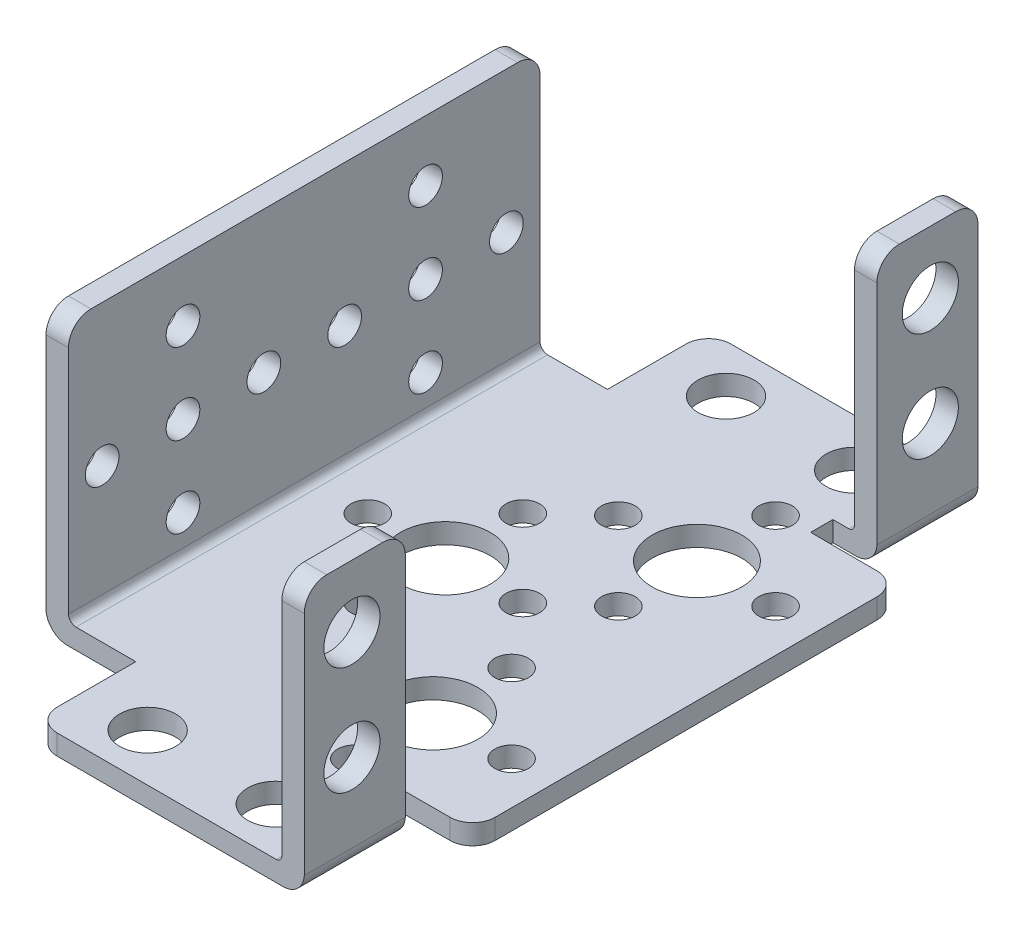
SolidWorks part; units mm, degrees
material "1060 Alloy"
ref_plane "Front Plane" through (0, 0, 0) normal (0, 0, 1) x (1, 0, 0)
ref_plane "Top Plane" through (0, 0, 0) normal (0, 1, 0) x (1, 0, 0)
ref_plane "Right Plane" through (0, 0, 0) normal (1, 0, 0) x (0, 0, -1)
sketch "Sketch2" plane through (0, 0, 0) normal (0, 0, 1) x (1, 0, 0)
  line L0 (1.7922, 0) -> (36, 0)
  line L1 (0, 1.7922) -> (0, 25)
  line L2 (0, 25) -> (2, 25)
  line L3 (2, 25) -> (2, 2.4579)
  line L4 (2.6657, 1.7922) -> (36, 1.7922)
  line L5 (36, 1.7922) -> (36, 0)
  arc A0 (2, 0) -> (0, 1.7922) centre (1.8961, 1.8961) cw
  arc A1 (2, 2.4579) -> (2.6657, 1.7922) centre (2.7075, 2.4997) ccw
extrude "Boss-Extrude1" add sketch "Sketch2" along normal blind 42 contours A1 L3 L2 L1 A0 L0 L5 L4
fillet "Fillet1" radius 2 4 edges at (36, 0.8961, 42) (36, 0.8961, 0) (1, 25, 0) (1, 25, 42)
sketch "Sketch3" plane through (0, 0, 0) normal (0, 0, -1) x (-1, 0, 0)
  line L1 (-2.6657, 1.7922) -> (-34, 1.7922) construction
  line L2 (-8, 1.7922) -> (-8, 0)
  line L3 (-1.7922, 0) -> (-34, 0) construction
  line L4 (-8, 0) -> (-30.2078, 0)
  line L5 (-32, 1.7922) -> (-32, 24)
  line L6 (-32, 24) -> (-30, 24)
  line L7 (-30, 24) -> (-30, 2.2866)
  line L8 (-29.5056, 1.7922) -> (-8, 1.7922)
  arc A0 (-30, 0) -> (-32, 1.7922) centre (-30.1039, 1.8961) cw
  arc A1 (-29.5056, 1.7922) -> (-30, 2.2866) centre (-29.4772, 2.315) cw
  line M8 (-2.6657, 1.7922) -> (-34, 1.7922)
  line M10 (-34, 0) -> (-1.7922, 0)
extrude "Boss-Extrude2" add sketch "Sketch3" along normal blind 9 contours A1 L7 L6 L5 M8 | A0 L4 L2 M10 M8
fillet "Fillet2" radius 2 3 edges at (8, 0.8961, -9) (31, 24, 0) (31, 24, -9)
sketch "Sketch4" plane through (0, 1.7922, 0) normal (0, 1, 0) x (1, 0, 0)
  line L1 (28.0756, 0) -> (28.0756, -1.9781)
  line L2 (28.0756, -1.9781) -> (36, -2)
  line L3 (34, 0) -> (28.0756, 0)
  arc A0 (36, -2) -> (34, 0) centre (34.0055, -1.9945) ccw
extrude "Cut-Extrude1" cut sketch "Sketch4" against normal blind 9
fillet "Fillet3" radius 2 1 edges
ref_plane "Plane1" through (0, 0, 21) normal (0, 0, -1) x (-1, 0, 0)
mirror "Mirror3" about plane through (0, 0, 21) normal (0, 0, -1) of "Fillet2", "Boss-Extrude2", "Cut-Extrude1", "Fillet3"
sketch "Sketch5" plane through (0, 0, 0) normal (-1, 0, 0) x (0, 0, 1)
  line L0 (41.4142, 24.4142) -> (41.4142, 12.4142) construction
  line L1 (42, 12.3961) -> (39, 12.3961) construction
  line L2 (42, 1.7922) -> (42, 23) construction
  line L3 (31.8, 12.3961) -> (31.8, 19.5961) construction
  line L4 (31.8, 12.3961) -> (31.8, 5.1961) construction
  line L5 (10.2, 12.3961) -> (10.2, 19.5961) construction
  line L6 (10.2, 12.3961) -> (10.2, 5.1961) construction
  arc A0 (42, 23) -> (40, 25) centre (40, 23) ccw construction
  circle A1 centre (39, 12.3961) radius 1.5
  circle A2 centre (31.8, 12.3961) radius 1.5
  circle A3 centre (24.6, 12.3961) radius 1.5
  circle A4 centre (17.4, 12.3961) radius 1.5
  circle A5 centre (10.2, 12.3961) radius 1.5
  circle A6 centre (3, 12.3961) radius 1.5
  circle A7 centre (31.8, 19.5961) radius 1.5
  circle A8 centre (31.8, 5.1961) radius 1.5
  circle A9 centre (10.2, 19.5961) radius 1.5
  circle A10 centre (10.2, 5.1961) radius 1.5
  dimension "D1" = 6
extrude "Cut-Extrude2" cut sketch "Sketch5" against normal blind 9 contours A2 | A1 | A3 | A4 | A5 | A6 | A7 | A9 | A10 | A8
sketch "Sketch7" plane through (0, 1.7922, 0) normal (0, 1, 0) x (1, 0, 0)
  circle A0 centre (25.2173, -46.7545) radius 2.5
  circle A1 centre (13.806, -46.7545) radius 2.5
extrude "Cut-Extrude3" cut sketch "Sketch7" against normal blind 9 contours A0 | A1
mirror "Mirror4" about plane through (0, 0, 21) normal (0, 0, -1) of "Cut-Extrude3"
sketch "Sketch8" plane through (30, 0, 0) normal (-1, 0, 0) x (0, 0, 1)
  circle A0 centre (46.7545, 18.4601) radius 2.5
  circle A1 centre (46.7545, 8.8011) radius 2.5
extrude "Cut-Extrude4" cut sketch "Sketch8" against normal blind 9 contours A0 | A1
mirror "Mirror5" about plane through (0, 0, 21) normal (0, 0, -1) of "Cut-Extrude4"
sketch "Sketch9" plane through (0, 1.7922, 0) normal (0, 1, 0) x (1, 0, 0)
  line L0 (25.2173, 4.7545) -> (25.2173, -9.2455) construction
  circle A0 centre (25.2173, -9.2455) radius 4
  circle A1 centre (25.2173, -2.2455) radius 1.5
  circle A2 centre (32.2173, -9.2455) radius 1.5
  circle A3 centre (25.2173, -16.2455) radius 1.5
  circle A4 centre (18.2173, -9.2455) radius 1.5
  point P19 (25.2173, -9.2455)
  dimension "D1" = 4
extrude "Cut-Extrude5" cut sketch "Sketch9" against normal blind 9 contours A0 | A2 | A4 | A3 | A1
mirror "Mirror6" about plane through (0, 0, 21) normal (0, 0, -1) of "Cut-Extrude5"
sketch "Sketch10" plane through (0, 1.7922, 0) normal (0, 1, 0) x (1, 0, 0)
  line L0 (13.806, 4.7545) -> (13.806, -20.2455) construction
  circle A0 centre (13.806, -20.2455) radius 4
  circle A1 centre (13.806, -13.3415) radius 1.5
  circle A2 centre (20.7101, -20.2455) radius 1.5
  circle A3 centre (13.806, -20.2455) radius 4
  circle A4 centre (13.806, -27.1496) radius 1.5
  circle A5 centre (13.806, -20.2455) radius 4
  circle A6 centre (6.902, -20.2455) radius 1.5
  circle A7 centre (13.806, -20.2455) radius 4
  point P18 (13.806, -20.2455)
  dimension "D1" = 4
extrude "Cut-Extrude6" cut sketch "Sketch10" against normal blind 9 contours A1 L0 | L0 A1 | A6 | A2 | A4 | A5
